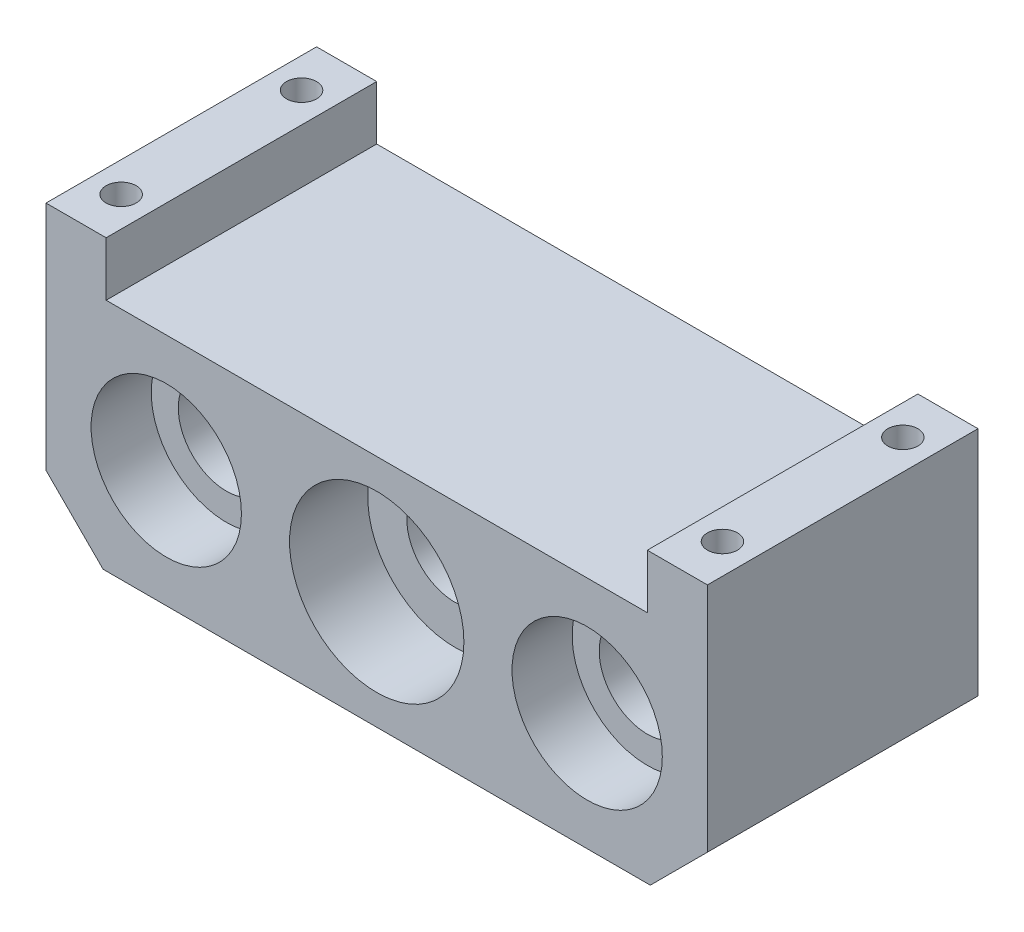
SolidWorks part; units mm, degrees
ref_plane "Front Plane" through (0, 0, 0) normal (0, 0, 1) x (1, 0, 0)
ref_plane "Top Plane" through (0, 0, 0) normal (0, 1, 0) x (1, 0, 0)
ref_plane "Right Plane" through (0, 0, 0) normal (1, 0, 0) x (0, 0, -1)
sketch "Sketch1" plane through (0, 0, 0) normal (0, 0, 1) x (1, 0, 0)
  line L0 (-45.5, 0) -> (45.5, 0)
  line L1 (45.5, 0) -> (55, 9.5)
  line L2 (55, 9.5) -> (55, 48)
  line L3 (55, 48) -> (45, 48)
  line L4 (45, 48) -> (45, 39)
  line L5 (45, 39) -> (-45, 39)
  line L6 (0, 39) -> (0, 0) construction
  line L7 (-45, 48) -> (-45, 39)
  line L8 (-55, 48) -> (-45, 48)
  line L9 (-55, 9.5) -> (-55, 48)
  line L10 (-45.5, 0) -> (-55, 9.5)
  dimension "D1" = 110
  dimension "D2" = 10
  dimension "D3" = 9
  dimension "D4" = 48
  dimension "D5" = 135
  dimension "D6" = 38.5
extrude "Boss-Extrude1" add sketch "Sketch1" along normal blind 45
sketch "Sketch2" plane through (0, 48, 0) normal (0, 1, 0) x (1, 0, 0)
  line L0 (0, 0) -> (0, 28.7176) construction
  line L1 (0, -22.5) -> (-17.4251, -22.5) construction
  line L2 (55, -45) -> (55, 0) construction
  circle A0 centre (-50, -7.5) radius 3 construction
  circle A2 centre (50, -7.5) radius 3 construction
  circle A3 centre (50, -37.5) radius 3 construction
  circle A4 centre (-50, -37.5) radius 3 construction
  point P15 (55, -22.5)
  dimension "D1" = 6
  dimension "D2" = 100
  dimension "D3" = 30
hole_wizard "M6x1.0 Tapped Hole1" positions "Sketch3" profile "Sketch4" tap size "M6x1.0" standard "ANSI Metric"
sketch "Sketch3" plane through (0, 48, 0) normal (0, 1, 0) x (1, 0, 0)
  point P0 (-50, -7.5)
  point P3 (50, -7.5)
  point P6 (50, -37.5)
  point P9 (-50, -37.5)
sketch "Sketch4" plane through (-50, 48, 7.5) normal (1, 0, 0) x (0, 0, 1)
  line L0 (0, 0) -> (0, 11.5022)
  line L1 (0, 11.5022) -> (2.5, 10)
  line L2 (2.5, 10) -> (2.5, 0)
  line L5 (2.5, 0) -> (0, 0)
  line L10 (0, 11.5022) -> (-2.5, 10) construction
  line L11 (0, -6.35) -> (0, 107.95) construction
  dimension "Tap Drill Dia." = 5
  dimension "Tap Drill Depth" = 10
  dimension "Drill Angle" = 118
cosmetic thread "Hole Thread1" parameters "D1"=12, "D2"=6
cosmetic thread "Hole Thread2" parameters "D1"=12, "D2"=6
cosmetic thread "Hole Thread11" parameters "D1"=12, "D2"=6
cosmetic thread "Hole Thread12" parameters "D1"=12, "D2"=6
sketch "Sketch5" plane through (0, 0, 45) normal (0, 0, 1) x (1, 0, 0)
  line L0 (45, 39) -> (-45, 39) construction
  line L2 (0, 39) -> (0, 0) construction
  circle A0 centre (-35, 19.5) radius 12.5
  circle A1 centre (0, 19.5) radius 14.5
  circle A2 centre (35, 19.5) radius 12.5
  point P6 (35, 32)
  point P8 (0, 19.5)
  point P11 (0, 34)
  point P12 (0, 0)
  point P15 (0, 0)
  point P16 (0, 0)
  dimension "D1" = 5
  dimension "D2" = 7
  dimension "D3" = 70
extrude "Cut-Extrude1" cut sketch "Sketch5" against normal blind 10
sketch "Sketch6" plane through (0, 0, 35) normal (0, 0, 1) x (1, 0, 0)
  circle A1 centre (0, 19.5) radius 14.5
  circle A2 centre (0, 19.5) radius 14.5
  dimension "D1" = 0
extrude "Cut-Extrude2" cut sketch "Sketch6" against normal blind 3
sketch "Sketch7" plane through (0, 0, 0) normal (0, 0, 1) x (1, 0, 0)
  circle A0 centre (0, 19.5) radius 8
  circle A1 centre (35, 19.5) radius 8
  circle A2 centre (-35, 19.5) radius 8
  dimension "D1" = 16
extrude "Cut-Extrude3" cut sketch "Sketch7" against normal through all and the other way through all
sketch "Sketch8" plane through (0, 0, 0) normal (0, 0, 1) x (1, 0, 0)
  circle A0 centre (19, 19.5) radius 3.2 construction
  circle A1 centre (0, 19.5) radius 8 construction
  circle A2 centre (0, 19.5) radius 8 construction
  point P5 (0, 0)
  dimension "D2" = 6.4
  dimension "D1" = 19
hole_wizard "M6x1.0 Tapped Hole2" positions "Sketch9" profile "Sketch11" tap size "M6x1.0" standard "ANSI Metric"
sketch "Sketch9" plane through (0, 0, 0) normal (0, 0, -1) x (-1, 0, 0)
  point P0 (-19, 19.5)
sketch "Sketch11" plane through (19, 19.5, 0) normal (1, 0, 0) x (0, 1, 0)
  line L0 (0, 0) -> (0, 16.5022)
  line L1 (0, 16.5022) -> (2.5, 15)
  line L2 (2.5, 15) -> (2.5, 0)
  line L5 (2.5, 0) -> (0, 0)
  line L10 (0, 16.5022) -> (-2.5, 15) construction
  line L11 (0, -6.35) -> (0, 107.95) construction
  dimension "Tap Drill Dia." = 5
  dimension "Tap Drill Depth" = 15
  dimension "Drill Angle" = 118
cosmetic thread "Hole Thread5" parameters "D1"=12, "D2"=6
pattern_circular "CirPattern1" count 8 over 360 about axis through (0, 19.5, 0) along (0, 0, 1) skipping 2, 6 of "M6x1.0 Tapped Hole2"
cosmetic thread "Hole Thread6" parameters "D1"=12, "D2"=6
cosmetic thread "Hole Thread7" parameters "D1"=12, "D2"=6
cosmetic thread "Hole Thread8" parameters "D1"=12, "D2"=6
cosmetic thread "Hole Thread9" parameters "D1"=12, "D2"=6
cosmetic thread "Hole Thread10" parameters "D1"=12, "D2"=6
